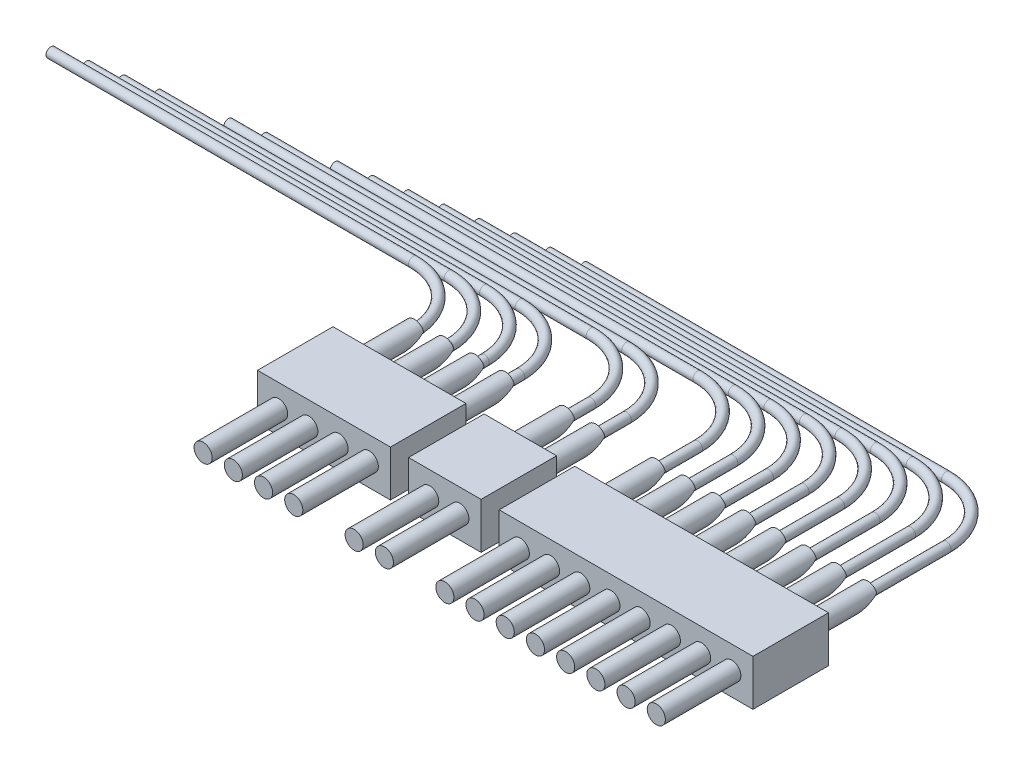
SolidWorks part; units mm, degrees
material "ASTM A36 Steel"
ref_plane "Front Plane" through (0, 0, 0) normal (0, 0, 1) x (1, 0, 0)
ref_plane "Top Plane" through (0, 0, 0) normal (0, 1, 0) x (1, 0, 0)
ref_plane "Right Plane" through (0, 0, 0) normal (1, 0, 0) x (0, 0, -1)
ref_plane "Plane1" through (0, 0, -4.445) normal (0, 0, 1) x (1, 0, 0)
sketch "Sketch1" plane through (0, 0, 0) normal (0, 1, 0) x (1, 0, 0)
  line L0 (-9.525, 3.175) -> (0.889, 5.0113) construction
  line L1 (-19.939, 3.175) -> (0.889, 3.175)
  line L2 (-19.939, 3.175) -> (-19.939, 0)
  line L3 (-19.939, 0) -> (0.889, 0)
  line L4 (0.889, 3.175) -> (0.889, 0)
  point P6 (-19.05, 0)
  dimension "D1" = 3.175
  dimension "D2" = 0.889
  dimension "D3" = 10
  dimension "D4" = 0.889
  dimension "D5" = 19.05
extrude "Boss-Extrude1" add sketch "Sketch1" against normal mid plane 1.9304
sketch "Sketch3" plane through (0, 0, 0) normal (0, 1, 0) x (1, 0, 0)
  line L0 (0, -2.0371) -> (0, -3.6246) construction
  line L1 (0, 5.715) -> (0.4064, 5.715)
  line L2 (0, 5.715) -> (0, -3.175)
  line L3 (0, -3.175) -> (0.381, -3.175)
  line L4 (0.4064, 5.715) -> (0.4064, 1.016)
  line L5 (-19.939, 3.175) -> (0.889, 3.175) construction
  line L6 (0.4064, 1.016) -> (0.381, 1.016)
  line L7 (0.381, 1.016) -> (0.381, -3.175)
  line L9 (-19.939, 0) -> (0.889, 0) construction
  dimension "D2" = 0.8128
  dimension "D3" = 2.54
  dimension "D4" = 3.175
  dimension "D5" = 1.016
  dimension "D6" = 0.762
revolve "Revolve1" add sketch "Sketch3" angle 360 about L0
sketch "Sketch4" plane through (0, 0, 0) normal (0, 1, 0) x (1, 0, 0)
  line L0 (0, 4.445) -> (0, 9.017)
  line L1 (-2.54, 11.557) -> (-17.78, 11.557)
  line L2 (-1.6667, 4.445) -> (1.6667, 4.445) construction
  arc A0 (0, 9.017) -> (-2.54, 11.557) centre (-2.54, 9.017) ccw
  dimension "D2" = 2.54
  dimension "D1" = 4.572
  dimension "D3" = 15.24
pattern_linear "LPattern1" count 17 spacing 1.27 along (-1, 0, 0) skipping (8, 0), (11, 0), (16, 0) of "Revolve1"
sketch "Sketch7" plane through (0, 0, 0) normal (1, 0, 0) x (0, 0, -1)
  line L0 (7.4056, -0.5197) -> (4.5609, -0.5197)
  line L1 (4.5609, -0.5197) -> (7.4056, 1.1227)
  line L2 (7.4056, 1.1227) -> (7.4056, -0.5197)
  point P2 (5.461, 0)
  dimension "D1" = 30
  dimension "D2" = 0.254
extrude "Cut-Extrude2" cut sketch "Sketch7" against normal through all and the other way through all
sketch "Sketch5" plane through (0, 0, -4.445) normal (0, 0, -1) x (-1, 0, 0)
  circle A0 centre (0, 0) radius 0.2032
  dimension "D1" = 0.4064
sweep "Sweep1" add profiles "Sketch5" path "Sketch4"
pattern_linear "LPattern2" count 17 spacing 1.2893 along (-0.9848, 0, 0.1736) skipping (8, 0), (11, 0), (16, 0) of "Sweep1"
sketch "Sketch6" plane through (0, 0, 0) normal (0, 1, 0) x (1, 0, 0)
  line L1 (-9.779, 6.096) -> (-10.541, 6.096)
  line L2 (-9.779, 6.096) -> (-9.779, -1.524)
  line L3 (-9.779, -1.524) -> (-10.541, -1.524)
  line L4 (-10.541, 6.096) -> (-10.541, -1.524)
  line L5 (-13.589, 6.096) -> (-14.351, 6.096)
  line L6 (-13.589, 6.096) -> (-13.589, -1.524)
  line L7 (-13.589, -1.524) -> (-14.351, -1.524)
  line L8 (-14.351, 6.096) -> (-14.351, -1.524)
  line L9 (-33.909, 6.096) -> (-34.671, 6.096) construction
  line L10 (-33.909, 6.096) -> (-33.909, -1.524) construction
  line L11 (-33.909, -1.524) -> (-34.671, -1.524) construction
  line L12 (-34.671, 6.096) -> (-34.671, -1.524) construction
  dimension "D1" = 1.524
  dimension "D2" = 7.62
  dimension "D3" = 0.762
  dimension "D4" = 9.779
  dimension "D5" = 20.32
  dimension "D6" = 3.81
extrude "Cut-Extrude1" cut sketch "Sketch6" against normal mid plane 5.08
